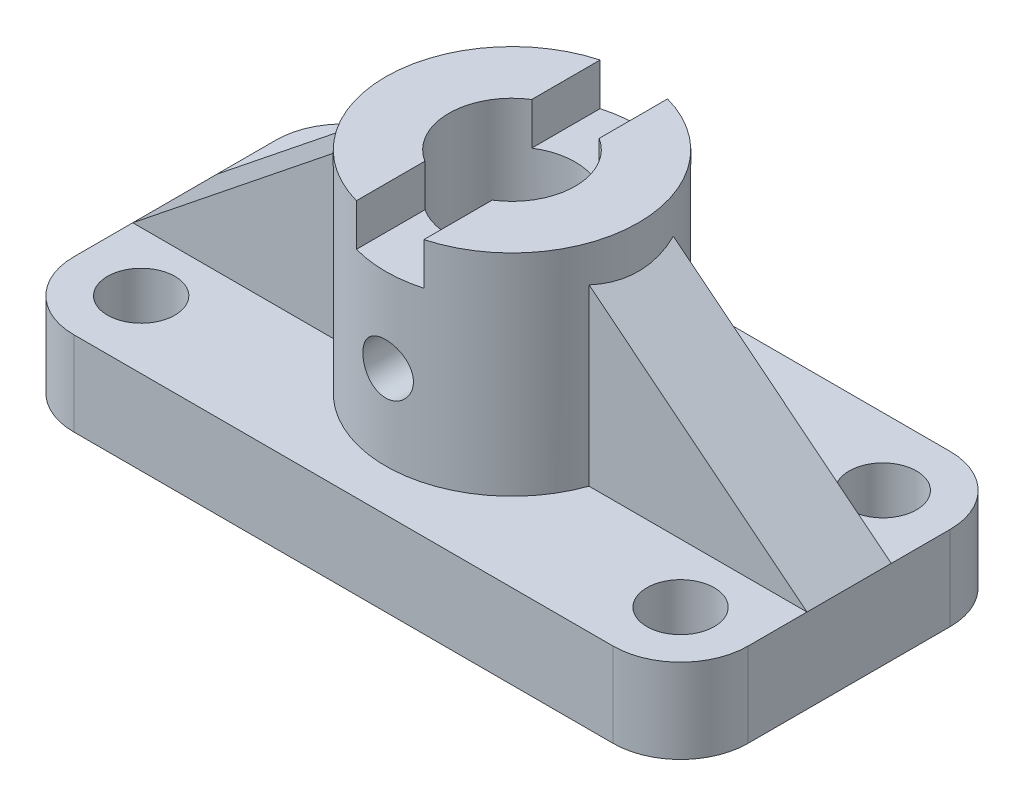
SolidWorks part; units mm, degrees
ref_plane "前视基准面" through (0, 0, 0) normal (0, 0, 1) x (1, 0, 0)
ref_plane "上视基准面" through (0, 0, 0) normal (0, 1, 0) x (1, 0, 0)
ref_plane "右视基准面" through (0, 0, 0) normal (1, 0, 0) x (0, 0, -1)
sketch "草图1" plane through (0, 0, 0) normal (0, 1, 0) x (1, 0, 0)
  line L1 (-40, 20) -> (40, 20)
  line L2 (-40, 20) -> (-40, -20)
  line L3 (-40, -20) -> (40, -20)
  line L4 (40, 20) -> (40, -20)
  line L5 (-40, 20) -> (40, -20) construction
  line L6 (-40, -20) -> (40, 20) construction
  point P0 (0, 0)
  dimension "D1" = 80
  dimension "D2" = 40
extrude "凸台-拉伸1" add sketch "草图1" along normal blind 10 contours L1 L4 L3 L2
fillet "圆角1" radius 8 4 edges at (-40, 5, -20) (-40, 5, 20) (40, 5, -20) (40, 5, 20)
sketch "草图2" plane through (0, 10, 0) normal (0, 1, 0) x (1, 0, 0)
  circle A0 centre (0, 0) radius 15
  circle A1 centre (0, 0) radius 7.5
  dimension "D1" = 15
  dimension "D2" = 30
extrude "凸台-拉伸2" add sketch "草图2" along normal blind 25 contours A1 | A0
sketch "草图3" plane through (0, 0, 0) normal (0, 0, 1) x (1, 0, 0)
  line L0 (15, 30) -> (40, 10)
  line L1 (15, 10) -> (15, 35) construction
  dimension "D1" = 5
rib "筋1" sketch "草图3" sketch "草图3" thickness 10 extrusion direction parallel to sketch draft on no parameters "D1"=10
mirror "镜向1" about plane through (0, 0, 0) normal (1, 0, 0) of "筋1"
sketch "草图4" plane through (0, 10, 0) normal (0, 1, 0) x (1, 0, 0)
  line L0 (32, 12) -> (40, 12) construction
  line L1 (32, 12) -> (32, 20) construction
  circle A1 centre (32, 12) radius 4
  dimension "D1" = 8
extrude "切除-拉伸1" cut sketch "草图4" against normal through all
mirror "镜向2" about plane through (0, 0, 0) normal (0, 0, 1) of "切除-拉伸1"
mirror "镜向3" about plane through (0, 0, 0) normal (1, 0, 0) of "切除-拉伸1"
mirror "镜向4" about plane through (0, 0, 0) normal (0, 0, 1) of "镜向3"
sketch "草图5" plane through (0, 35, 0) normal (0, 1, 0) x (1, 0, 0)
  line L1 (-4, 15.6496) -> (4, 15.6496)
  line L2 (-4, 15.6496) -> (-4, -15.6496)
  line L3 (-4, -15.6496) -> (4, -15.6496)
  line L4 (4, 15.6496) -> (4, -15.6496)
  line L5 (-4, 15.6496) -> (4, -15.6496) construction
  line L6 (-4, -15.6496) -> (4, 15.6496) construction
  point P0 (0, 0)
  dimension "D1" = 8
extrude "切除-拉伸2" cut sketch "草图5" against normal blind 5 contours L1 L4 L3 L2
sketch "草图6" plane through (0, 0, 0) normal (0, 0, 1) x (1, 0, 0)
  line L0 (0, -1.771) -> (0, 34.2705) construction
  circle A0 centre (0, 20) radius 3
  dimension "D1" = 6
  dimension "D2" = 20
extrude "切除-拉伸4" cut sketch "草图6" against normal through all both and the other way through all contours A0
